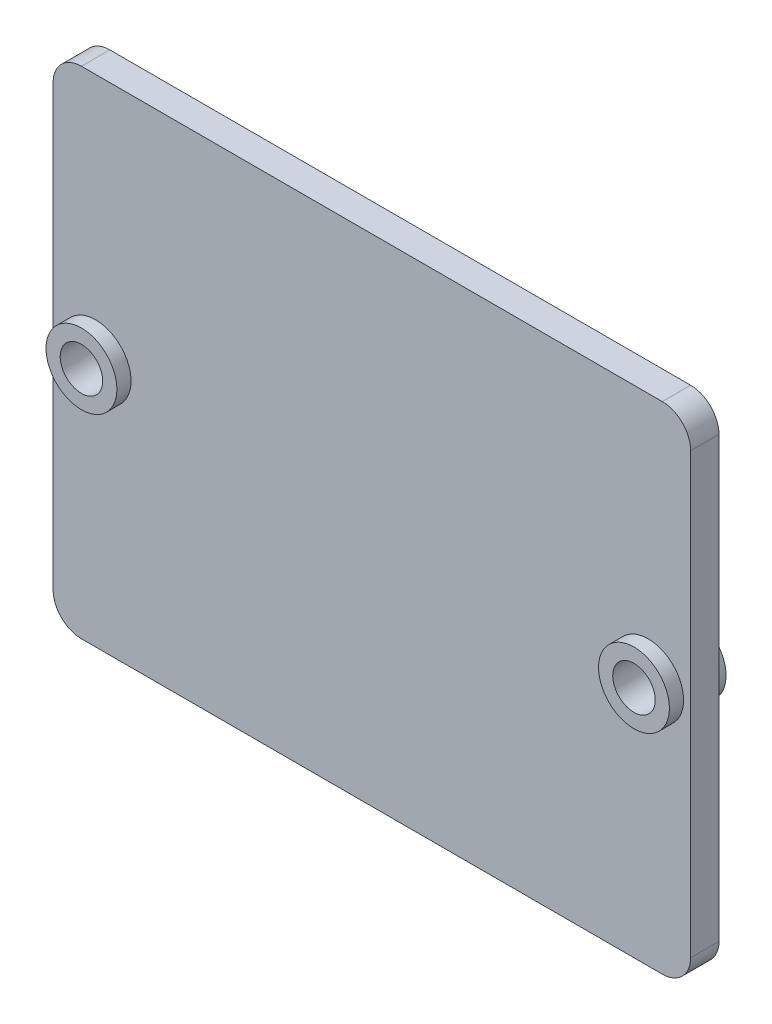
SolidWorks part; units mm, degrees
ref_plane "Front Plane" through (0, 0, 0) normal (0, 0, 1) x (1, 0, 0)
ref_plane "Top Plane" through (0, 0, 0) normal (0, 1, 0) x (1, 0, 0)
ref_plane "Right Plane" through (0, 0, 0) normal (1, 0, 0) x (0, 0, -1)
sketch "Sketch1" plane through (0, 0, 0) normal (0, 0, 1) x (1, 0, 0)
  line L1 (0, 0) -> (450, 0)
  line L2 (0, 0) -> (0, -350)
  line L3 (0, -350) -> (450, -350)
  line L4 (450, 0) -> (450, -350)
  dimension "D1" = 450
  dimension "D2" = 350
extrude "Boss-Extrude1" add sketch "Sketch1" along normal blind 20
sketch "Sketch2" plane through (0, 0, 0) normal (0, 0, -1) x (-1, 0, 0)
  line L0 (-450, -350) -> (-450, 0) construction
  line L1 (0, 0) -> (0, -350) construction
  line L2 (-450, 0) -> (0, 0) construction
  circle A0 centre (-420, -175) radius 15
  circle A1 centre (-30, -175) radius 15
  dimension "D1" = 30
  dimension "D2" = 30
  dimension "D3" = 30
  dimension "D4" = 30
  dimension "D5" = 175
  dimension "D6" = 175
extrude "Cut-Extrude1" cut sketch "Sketch2" against normal blind 25 contours A1 | A0
sketch "Sketch3" plane through (0, 0, 0) normal (0, 0, -1) x (-1, 0, 0)
  circle A0 centre (-420, -175) radius 25
  circle A1 centre (-30, -175) radius 25
  circle A2 centre (-420, -175) radius 15
  circle A3 centre (-30, -175) radius 15
extrude "Boss-Extrude2" add sketch "Sketch3" along normal blind 10 and the other way blind 30 contours A0 | A1 | A2 | A3
fillet "Fillet1" radius 20 4 edges at (0, -350, 10) (450, -350, 10) (0, 0, 10) (450, 0, 10)
